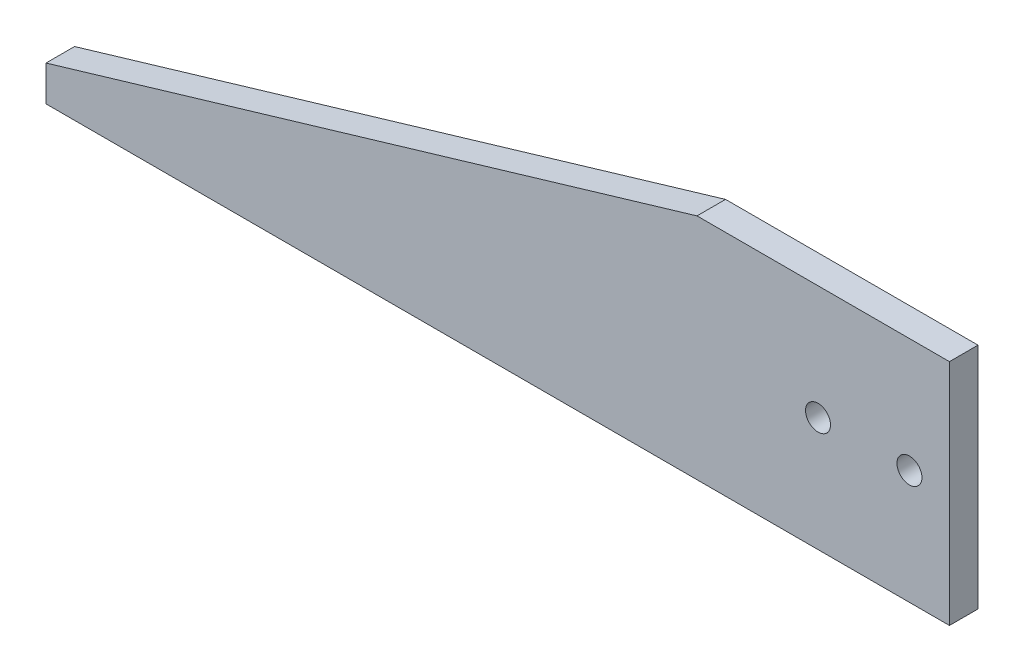
SolidWorks part; units mm, degrees
ref_plane "Front Plane" through (0, 0, 0) normal (0, 0, 1) x (1, 0, 0)
ref_plane "Top Plane" through (0, 0, 0) normal (0, 1, 0) x (1, 0, 0)
ref_plane "Right Plane" through (0, 0, 0) normal (1, 0, 0) x (0, 0, -1)
sketch "Sketch1" plane through (0, 0, 0) normal (0, 0, 1) x (1, 0, 0)
  line L0 (0, 0) -> (0, 50.8)
  line L1 (0, 50.8) -> (-56.1155, 50.8)
  line L2 (-56.1155, 50.8) -> (-200.8362, 7.8695)
  line L3 (-200.8362, 7.8695) -> (-200.8362, 0)
  line L4 (-200.8362, 0) -> (0, 0)
  dimension "D1" = 50.8
extrude "Boss-Extrude1" add sketch "Sketch1" along normal blind 6.35
sketch "Sketch2" plane through (0, 0, 6.35) normal (0, 0, 1) x (1, 0, 0)
  line L0 (0, 25.4) -> (-43.8797, 25.4) construction
  line L1 (0, 0) -> (0, 50.8) construction
  circle A0 centre (-29.21, 25.4) radius 2.7781
  circle A1 centre (-8.89, 25.4) radius 2.7781
  dimension "D1" = 5.5562
  dimension "D2" = 8.89
  dimension "D3" = 20.32
extrude "Cut-Extrude1" cut sketch "Sketch2" against normal through all
